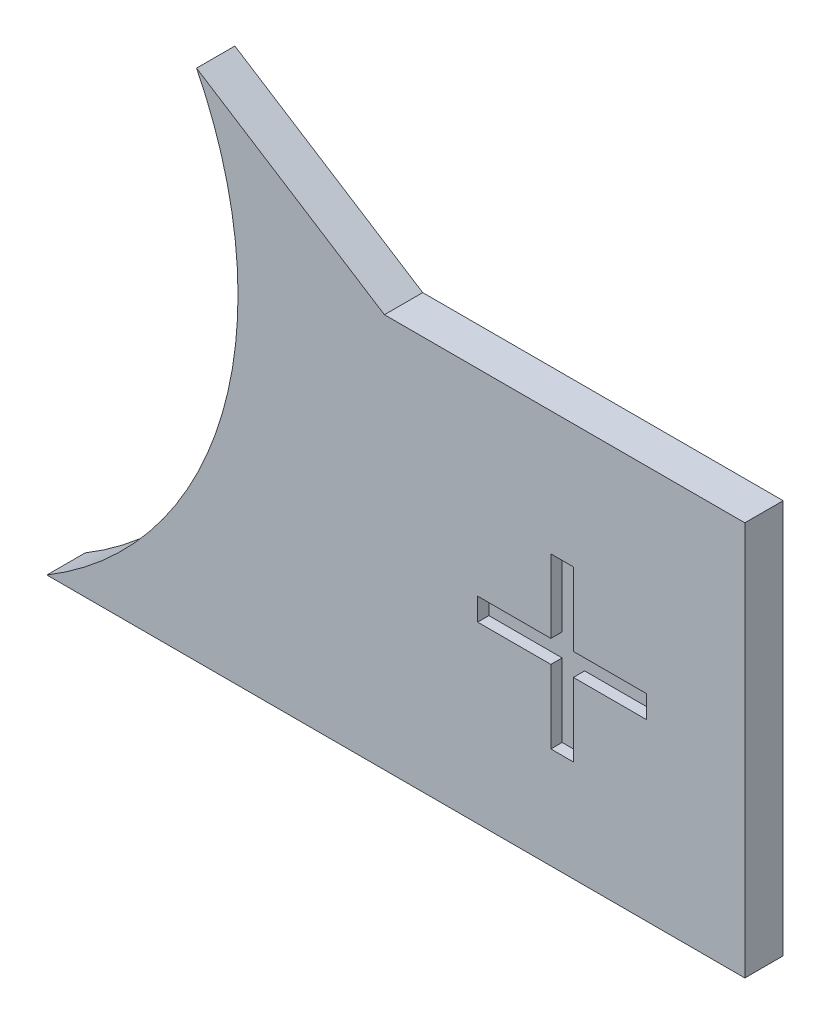
SolidWorks part; units mm, degrees
ref_plane "前视基准面" through (0, 0, 0) normal (0, 0, 1) x (1, 0, 0)
ref_plane "上视基准面" through (0, 0, 0) normal (0, 1, 0) x (1, 0, 0)
ref_plane "右视基准面" through (0, 0, 0) normal (1, 0, 0) x (0, 0, -1)
sketch "Sketch1" plane through (0, 0, 0) normal (0, 0, 1) x (1, 0, 0)
  line L0 (0, -30) -> (80, -30)
  line L1 (80, -30) -> (80, 5)
  line L2 (80, 5) -> (48, 5)
  line L4 (48, 5) -> (16.1141, 25.3049)
  arc A0 (16.1141, 25.3049) -> (0, -30) centre (0, 0) ccw
  dimension "D1" = 80
  dimension "D2" = 60
  dimension "D3" = 35
  dimension "D4" = 32
extrude "Boss-Extrude1" add sketch "Sketch1" along normal blind 3.4
sketch "Sketch2" plane through (0, 0, 3.4) normal (0, 0, 1) x (1, 0, 0)
  circle A0 centre (48, -12.5) radius 2.75
  circle A3 centre (48, -12.5) radius 2
  dimension "D2" = 5.5
sketch "Sketch3" plane through (0, 0, 3.4) normal (0, 0, 1) x (1, 0, 0)
  circle A0 centre (0, 0) radius 5
  dimension "D1" = 10
extrude "Cut-Extrude1" cut sketch "Sketch3" against normal blind 6
sketch "Sketch5" plane through (0, 0, 3.4) normal (0, 0, 1) x (1, 0, 0)
  line L0 (0, 20) -> (0, 0) construction
  line L1 (0, 0) -> (-18.1865, -10.5) construction
  arc A0 (0, 10) -> (-8.6603, -5) centre (0, 0) ccw
  arc A2 (0, 18) -> (-15.5885, -9) centre (0, 0) ccw
  arc A3 (-8.6603, -5) -> (-15.5885, -9) centre (-12.1244, -7) cw
  arc A4 (0, 18) -> (0, 10) centre (0, 14) cw
  point P4 (0, 18)
  point P6 (0, 10)
  point P8 (-8.6603, -5)
  point P9 (-15.5885, -9)
  dimension "D1" = 120
  dimension "D2" = 21
extrude "Cut-Extrude2" cut sketch "Sketch5" against normal blind 10
sketch "Sketch6" plane through (0, 0, 0) normal (0, 0, -1) x (-1, 0, 0)
  circle A0 centre (0, 0) radius 35
extrude "Cut-Extrude3" cut sketch "Sketch6" against normal blind 10
sketch "Sketch7" plane through (0, 0, 3.4) normal (0, 0, 1) x (1, 0, 0)
  line L0 (62.7754, -14.5) -> (62.7754, -21)
  line L1 (64.7754, -6) -> (62.7754, -6)
  line L2 (64.7754, -6) -> (64.7754, -12.5)
  line L3 (64.7754, -21) -> (62.7754, -21)
  line L4 (62.7754, -6) -> (62.7754, -12.5)
  line L7 (80, -30) -> (80, 5) construction
  line L8 (62.7754, -12.5) -> (56.2754, -12.5)
  line L9 (71.2754, -12.5) -> (64.7754, -12.5)
  line L10 (71.2754, -12.5) -> (71.2754, -14.5)
  line L11 (71.2754, -14.5) -> (64.7754, -14.5)
  line L12 (56.2754, -12.5) -> (56.2754, -14.5)
  line L17 (62.7754, -14.5) -> (56.2754, -14.5)
  line L18 (63.9087, -14.5) -> (63.642, -14.5)
  line L19 (64.7754, -14.5) -> (64.7754, -21)
  point P0 (63.9087, -12.5)
  point P9 (80, -12.5)
  point P10 (63.7754, -13.5)
  dimension "D1" = 15
  dimension "D2" = 2
  dimension "D3" = 0
  dimension "D4" = 2
  dimension "D5" = 15
extrude "Cut-Extrude4" cut sketch "Sketch7" against normal blind 1
